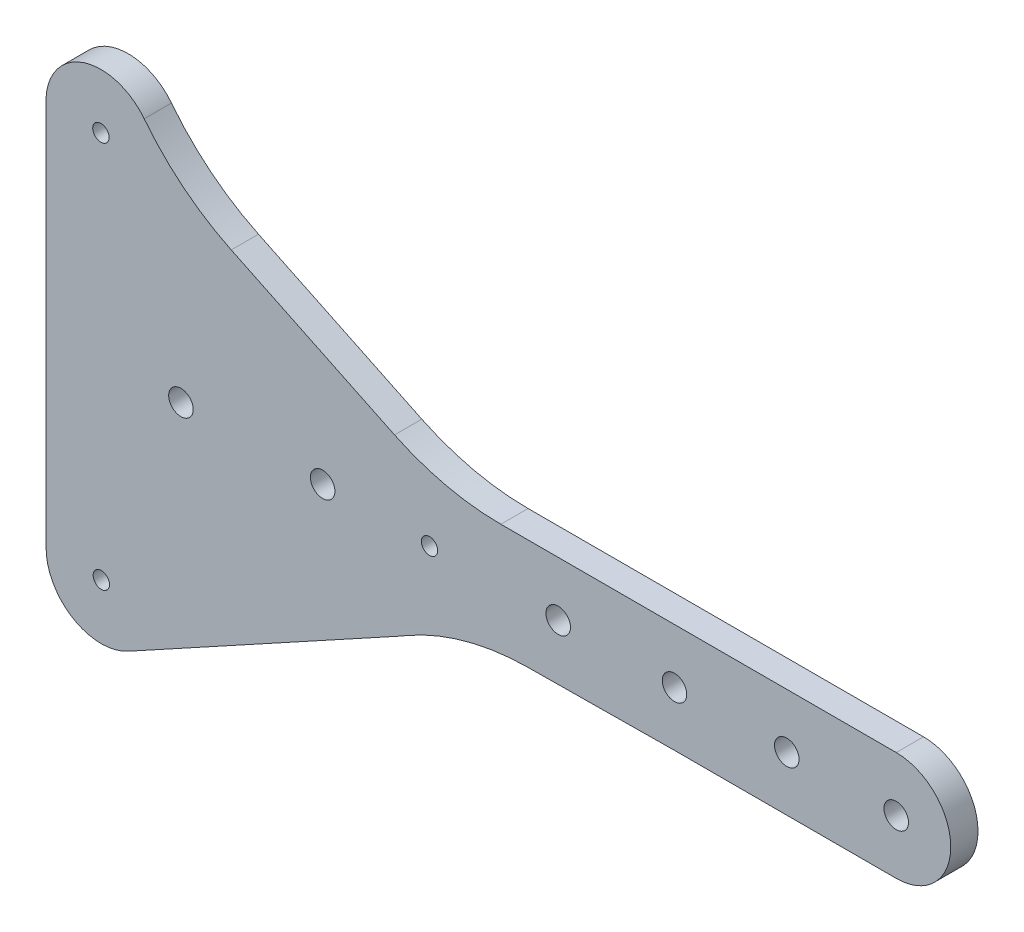
SolidWorks part; units mm, degrees
ref_plane "Alzado" through (0, 0, 0) normal (0, 0, 1) x (1, 0, 0)
ref_plane "Planta" through (0, 0, 0) normal (0, 1, 0) x (1, 0, 0)
ref_plane "Vista lateral" through (0, 0, 0) normal (1, 0, 0) x (0, 0, -1)
ref_plane "Plano1" through (0, 0, 0) normal (0, 0, -1) x (-1, 0, 0)
sketch "Croquis1" plane through (0, 0, 0) normal (0, 0, -1) x (-1, 0, 0)
  line L0 (-71.341, -16.3634) -> (-70.4194, -16.8998)
  line L1 (-39.2255, 28.8515) -> (-69.1843, 14.4452)
  line L3 (-120.5435, 10) -> (-161.2211, 10)
  line L5 (-120.5435, -10) -> (-161.2211, -10)
  line L8 (-88.6859, 10) -> (-120.5435, 10)
  line L9 (-120.5435, -10) -> (-93.5479, -10.2576)
  line L11 (-20.27, -44.3856) -> (-70.4194, -16.8998)
  line L15 (-5.2673, -35.5) -> (-5.2673, 34.7082)
  circle A0 centre (-30, 0) radius 2.25
  circle A1 centre (-15.4, -35.5) radius 2.55
  circle A2 centre (-15.3179, 35.5) radius 2.55
  arc A3 (-23.2632, 41.7059) -> (-39.2255, 28.8515) centre (-58.7271, 69.4063) cw
  arc A4 (-69.1843, 14.4452) -> (-88.6859, 10) centre (-88.6859, 55) cw
  circle A5 centre (-141.1438, 0) radius 2.25
  circle A6 centre (-161.2211, 0) radius 2.25
  arc A7 (-161.2211, 10) -> (-161.2211, -10) centre (-161.2211, 0) ccw
  circle A8 centre (-56, 0) radius 2.25
  arc A11 (-93.5479, -10.2576) -> (-71.341, -16.3634) centre (-93.9772, -55.2555) cw
  arc A13 (-20.27, -44.3856) -> (-5.2673, -35.5) centre (-15.4, -35.5) ccw
  arc A14 (-5.2673, 34.7082) -> (-23.2632, 41.7059) centre (-15.3179, 35.5) ccw
  circle A18 centre (-75.6, 0) radius 1.5
  circle A19 centre (-99.2101, 0) radius 2.25
  circle A20 centre (-120.5435, 0) radius 2.25
  point P10 (-25.3996, 35.5)
  dimension "D1" = 45
  dimension "D2" = 45
  dimension "D4" = 45
extrude "Saliente-Extruir1" add sketch "Croquis1" against normal blind 5
sketch "Croquis2" plane through (0, 0, 5) normal (0, 0, 1) x (1, 0, 0)
  circle A0 centre (15.4, -35.5) radius 2.55
  circle A1 centre (15.4, -35.5) radius 1.5
  circle A2 centre (15.3179, 35.5) radius 2.55
  circle A3 centre (15.3179, 35.5) radius 1.5
  dimension "D1" = 5.1
  dimension "D2" = 3
  dimension "D3" = 5.1
  dimension "D4" = 3
extrude "Saliente-Extruir2" add sketch "Croquis2" against normal up to surface (5 mm away) up to face at (122.7935, 0, 0)
